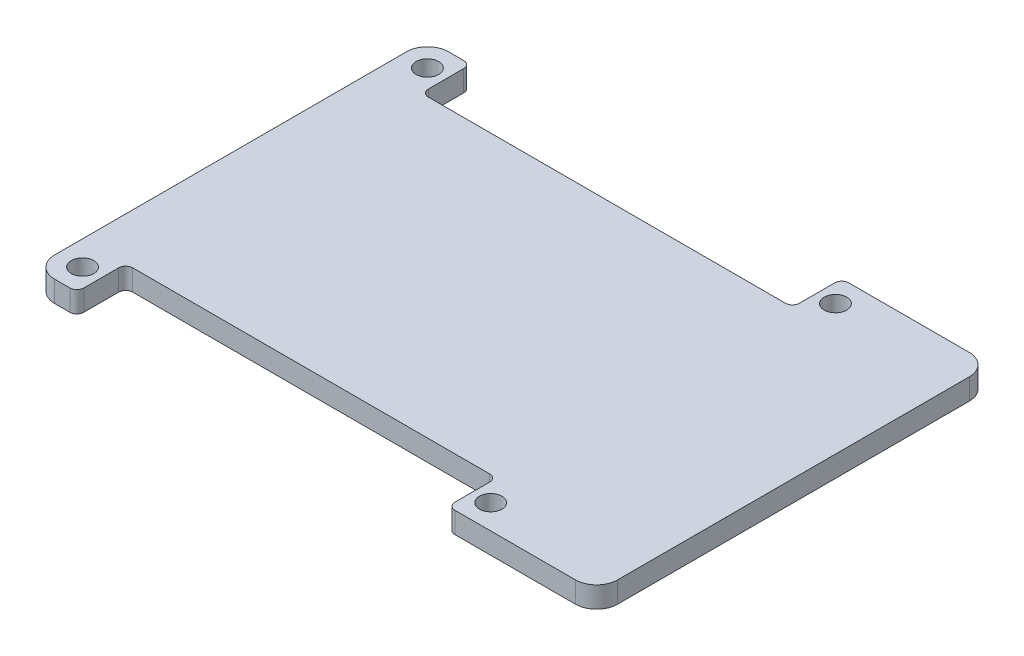
SolidWorks part; units mm, degrees
material "有机玻璃 (TM) GS 丙烯酸铸钣"
ref_plane "前视基准面" through (0, 0, 0) normal (0, 0, 1) x (1, 0, 0)
ref_plane "上视基准面" through (0, 0, 0) normal (0, 1, 0) x (1, 0, 0)
ref_plane "右视基准面" through (0, 0, 0) normal (1, 0, 0) x (0, 0, -1)
other "Configuration Table"
sketch "草图1" plane through (0, 0, 0) normal (0, 1, 0) x (1, 0, 0)
  line L0 (-21.1346, 23.39) -> (-21.1346, 18.3777)
  line L5 (-22.1346, 17.3777) -> (-72.8747, 17.3777)
  line L6 (-73.8747, 18.3777) -> (-73.8747, 23.39)
  line L7 (-22.1346, 21.0502) -> (-22.1346, 23.2653) construction
  line L12 (-80.009, 21.4027) -> (-80.009, -28.6044)
  line L13 (-77.0217, -31.5917) -> (12.7873, -31.5917)
  line L14 (15.7746, -28.6044) -> (15.7746, 21.4027)
  line L15 (12.7873, 24.39) -> (-77.0217, 24.39)
  line L16 (-80.009, 21.4027) -> (-80.009, -28.6044)
  line L17 (-77.0217, -31.5917) -> (-74.8747, -31.5917)
  line L19 (-3.009, 24.39) -> (-20.1346, 24.39)
  line L20 (-22.2671, 18.3777) -> (-24.4822, 18.3777) construction
  line L21 (-72.8747, 23.2653) -> (-72.8747, 21.0502) construction
  line L22 (-74.8747, 24.39) -> (-77.0217, 24.39)
  line L23 (-73.8747, 18.3777) -> (-73.8747, -36.7236) construction
  line L24 (-73.8747, -30.5917) -> (-73.8747, -25.645)
  line L25 (-72.8747, -24.645) -> (-22.1346, -24.645)
  line L26 (-21.1346, -25.645) -> (-21.1346, -30.5917)
  line L27 (-20.1346, -31.5917) -> (-3.009, -31.5917)
  line L28 (-80.009, -21.7605) -> (-0.009, -21.7605) construction
  line L29 (-0.009, -21.7605) -> (-0.009, 21.39)
  line L30 (-0.009, -21.7605) -> (-0.009, -28.5917)
  arc A0 (-74.8747, 24.39) -> (-73.8747, 23.39) centre (-74.8747, 23.39) cw
  arc A1 (-73.8747, 18.3777) -> (-72.8747, 17.3777) centre (-72.8747, 18.3777) ccw
  arc A2 (-22.1346, 17.3777) -> (-21.1346, 18.3777) centre (-22.1346, 18.3777) ccw
  arc A3 (-21.1346, 23.39) -> (-20.1346, 24.39) centre (-20.1346, 23.39) cw
  circle A4 centre (-76.5285, 20.8867) radius 1.6
  circle A5 centre (-18.5286, 20.8866) radius 1.6
  circle A6 centre (-18.5283, -28.1137) radius 1.6
  circle A7 centre (-76.5283, -28.1135) radius 1.6
  arc A8 (-80.009, -28.6044) -> (-77.0217, -31.5917) centre (-77.0217, -28.6044) ccw
  arc A9 (12.7873, -31.5917) -> (15.7746, -28.6044) centre (12.7873, -28.6044) ccw
  arc A10 (15.7746, 21.4027) -> (12.7873, 24.39) centre (12.7873, 21.4027) ccw
  arc A11 (-77.0217, 24.39) -> (-80.009, 21.4027) centre (-77.0217, 21.4027) ccw
  arc A12 (-80.009, -28.6044) -> (-77.0217, -31.5917) centre (-77.0217, -28.6044) ccw
  arc A15 (-77.0217, 24.39) -> (-80.009, 21.4027) centre (-77.0217, 21.4027) ccw
  arc A20 (-74.8747, -31.5917) -> (-73.8747, -30.5917) centre (-74.8747, -30.5917) ccw
  arc A21 (-73.8747, -25.645) -> (-72.8747, -24.645) centre (-72.8747, -25.645) cw
  arc A22 (-22.1346, -24.645) -> (-21.1346, -25.645) centre (-22.1346, -25.645) cw
  arc A23 (-21.1346, -30.5917) -> (-20.1346, -31.5917) centre (-20.1346, -30.5917) ccw
  arc A24 (-0.009, 21.39) -> (-3.009, 24.39) centre (-3.009, 21.39) ccw
  arc A25 (-0.009, -28.5917) -> (-3.009, -31.5917) centre (-3.009, -28.5917) cw
  point P49 (-73.8747, -31.5917)
  point P52 (-73.8747, -24.645)
  point P57 (-21.1346, -31.5917)
  dimension "D2" = 3.2
  dimension "D3" = 3.2
  dimension "D4" = 3.2
  dimension "D5" = 3.2
  dimension "D6" = 1
  dimension "D7" = 1
  dimension "D9" = 1
  dimension "D10" = 1
  dimension "D11" = 3
  dimension "D12" = 3
  dimension "D1" = 0
  dimension "D8" = 1
extrude "凸台-拉伸1" add sketch "草图1" along normal blind 3
